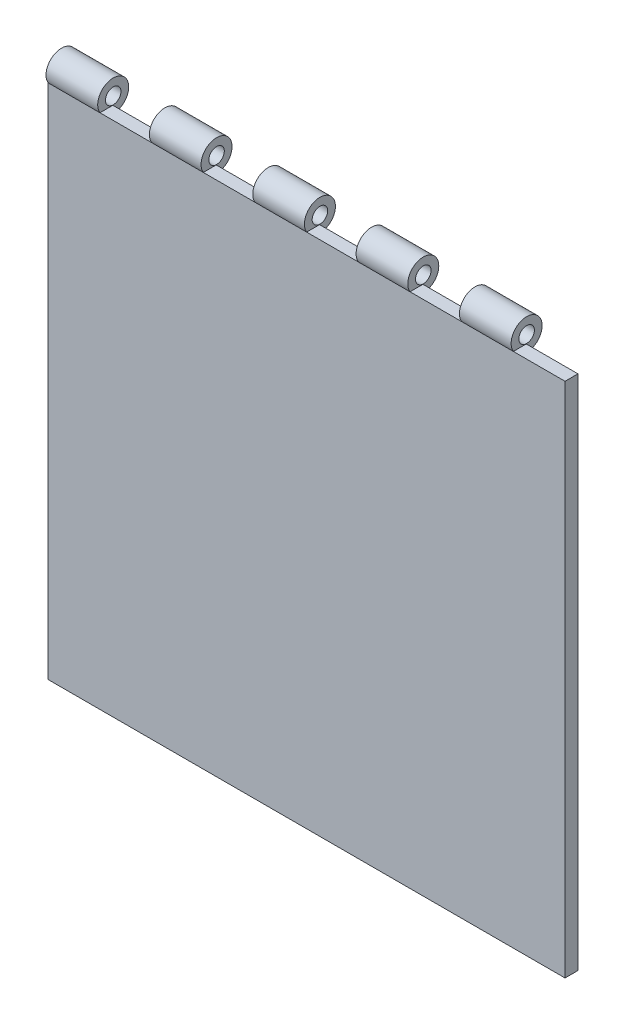
SolidWorks part; units mm, degrees
material "Acrylic (Medium-high impact)"
ref_plane "Front Plane" through (0, 0, 0) normal (0, 0, 1) x (1, 0, 0)
ref_plane "Top Plane" through (0, 0, 0) normal (0, 1, 0) x (1, 0, 0)
ref_plane "Right Plane" through (0, 0, 0) normal (1, 0, 0) x (0, 0, -1)
sketch "Sketch1" plane through (0, 0, 0) normal (0, 0, 1) x (1, 0, 0)
  line L1 (0, 0) -> (254, 0)
  line L2 (0, 0) -> (0, 254)
  line L3 (0, 254) -> (254, 254)
  line L4 (254, 0) -> (254, 254)
  dimension "D1" = 254
  dimension "D2" = 254
extrude "Boss-Extrude1" add sketch "Sketch1" along normal mid plane 6.35
sketch "Sketch2" plane through (0, 0, 0) normal (-1, 0, 0) x (0, 0, 1)
  circle A0 centre (-3.3554, 257.9265) radius 7.62
  circle A1 centre (-3.3554, 257.9265) radius 3.81
  dimension "D1" = 15.24
  dimension "D2" = 7.62
extrude "Boss-Extrude2" add sketch "Sketch2" against normal blind 25.4
pattern_linear "LPattern1" count 5 spacing 50.8 along (1, 0, 0) of "Boss-Extrude2"
scale "Scale1" bodies to scale 103 scale about centroid uniform scaling yes scale factor 0.9
